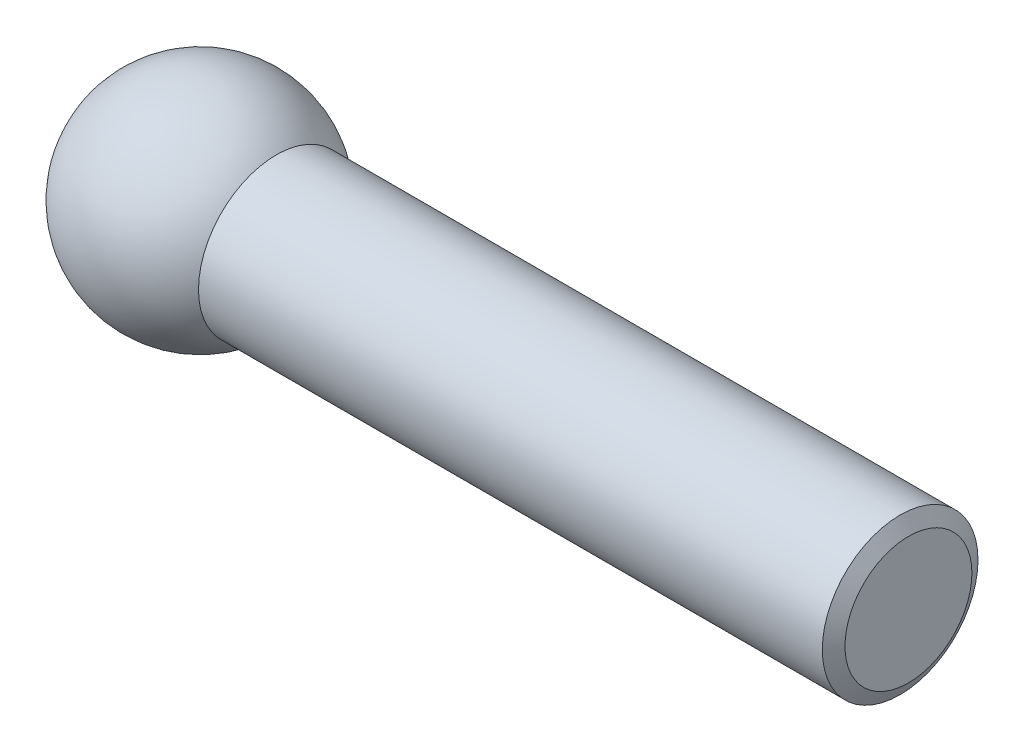
SolidWorks part; units mm, degrees
ref_plane "Front Plane" through (0, 0, 0) normal (0, 0, 1) x (1, 0, 0)
ref_plane "Top Plane" through (0, 0, 0) normal (0, 1, 0) x (1, 0, 0)
ref_plane "Right Plane" through (0, 0, 0) normal (1, 0, 0) x (0, 0, -1)
sketch "Sketch1" plane through (0, 0, 0) normal (1, 0, 0) x (0, 0, -1)
  circle A0 centre (0, 0) radius 14.2875
  dimension "D1" = 28.575
extrude "Boss-Extrude1" add sketch "Sketch1" along normal blind 130
ref_plane "Plane1" through (131.016, 0, 0) normal (1, 0, 0) x (0, 0, -1)
chamfer "Chamfer1" distance 1.524 angle 60 1 edges at (130, 0, -14.2875)
sketch "Sketch4" plane through (0, 0, 0) normal (0, 0, 1) x (1, 0, 0)
  line L0 (0, 14.2875) -> (0, -14.2875) construction
  line L1 (-20, 0) -> (20, 0)
  line L2 (0, 0) -> (46.2038, 0) construction
  arc A0 (20, 0) -> (-20, 0) centre (0, 0) ccw
  dimension "D1" = 40
revolve "Revolve1" add sketch "Sketch4" angle 360 about L2
ref_plane "Plane2" through (81, 0, 0) normal (1, 0, 0) x (0, 0, -1)
sketch "Sketch5" plane through (81, 0, 0) normal (1, 0, 0) x (0, 0, -1)
  circle A0 centre (0, 0) radius 14.2875 construction
  circle A1 centre (0, 0) radius 14.2875
